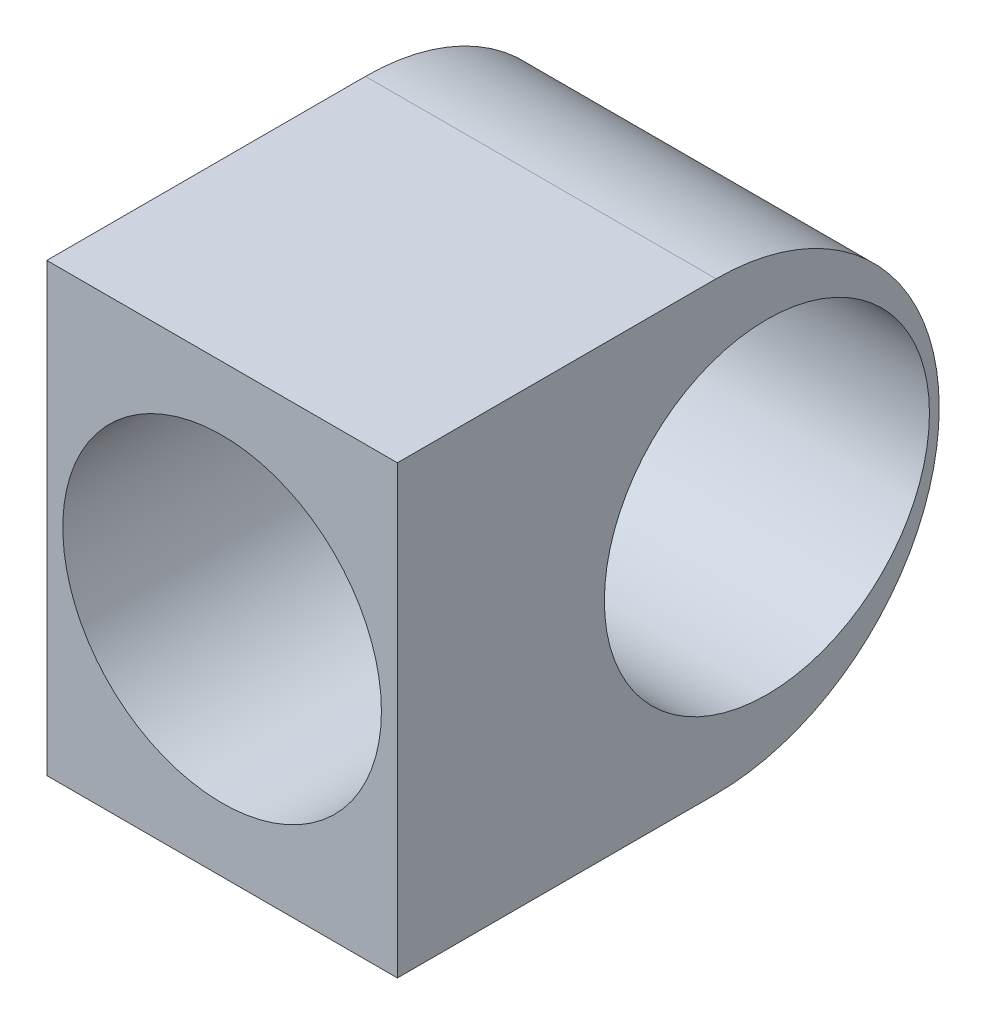
SolidWorks part; units mm, degrees
material "Rubber"
ref_plane "Front Plane" through (0, 0, 0) normal (0, 0, 1) x (1, 0, 0)
ref_plane "Top Plane" through (0, 0, 0) normal (0, 1, 0) x (1, 0, 0)
ref_plane "Right Plane" through (0, 0, 0) normal (1, 0, 0) x (0, 0, -1)
sketch "Sketch1" plane through (0, 0, 0) normal (0, 0, 1) x (1, 0, 0)
  line L0 (0, 0) -> (0, 7)
  line L1 (0, 7) -> (5.5, 7)
  line L2 (5.5, 7) -> (5.5, 0)
  line L3 (5.5, 0) -> (0, 0)
extrude "Boss-Extrude1" add sketch "Sketch1" along normal blind 5
sketch "Sketch3" plane through (5.5, 0, 0) normal (1, 0, 0) x (0, 0, -1)
  line L0 (0, 7) -> (0, 0)
  arc A0 (0, 7) -> (0, 0) centre (0, 3.5) cw
extrude "Boss-Extrude2" add sketch "Sketch3" against normal blind 5.5
sketch "Sketch4" plane through (0, 0, 0) normal (-1, 0, 0) x (0, 0, 1)
  circle A0 centre (-0.7971, 3.5) radius 2.55
extrude "Cut-Extrude1" cut sketch "Sketch4" against normal through all
sketch "Sketch5" plane through (0, 0, 5) normal (0, 0, 1) x (1, 0, 0)
  line L0 (0, 7) -> (5.5, 0)
  circle A0 centre (2.75, 3.5) radius 2.4994
extrude "Cut-Extrude2" cut sketch "Sketch5" against normal blind 4 contours A0
